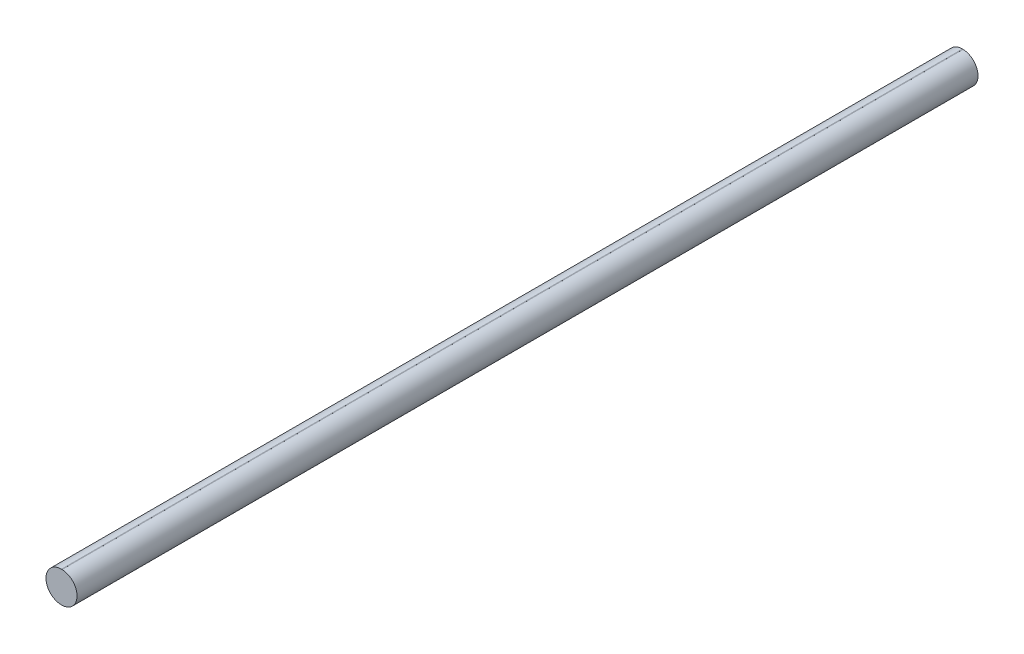
SolidWorks part; units mm, degrees
material "6061 Alloy"
ref_plane "Front Plane" through (0, 0, 0) normal (0, 0, 1) x (1, 0, 0)
ref_plane "Top Plane" through (0, 0, 0) normal (0, 1, 0) x (1, 0, 0)
ref_plane "Right Plane" through (0, 0, 0) normal (1, 0, 0) x (0, 0, -1)
sketch "Sketch2" plane through (0, 0, 0) normal (0, 0, 1) x (1, 0, 0)
  circle A0 centre (0, 0) radius 3.175
  dimension "D1" = 6.35
extrude "Boss-Extrude1" add sketch "Sketch2" along normal blind 184.15
sketch "Sketch4" plane through (0, 0, 184.15) normal (0, 0, 1) x (1, 0, 0)
  line L1 (0, 3.175) -> (0.1236, 3.175)
  line L2 (0, 3.175) -> (0, -3.1726)
  line L3 (0, -3.1726) -> (0.1236, -3.1726)
  line L4 (0.1236, 3.175) -> (0.1236, -3.1726)
  circle A0 centre (0, 0) radius 3.175 construction
  point P0 (0, 0)
extrude "Boss-Extrude2" add sketch "Sketch4" against normal blind 184.15
